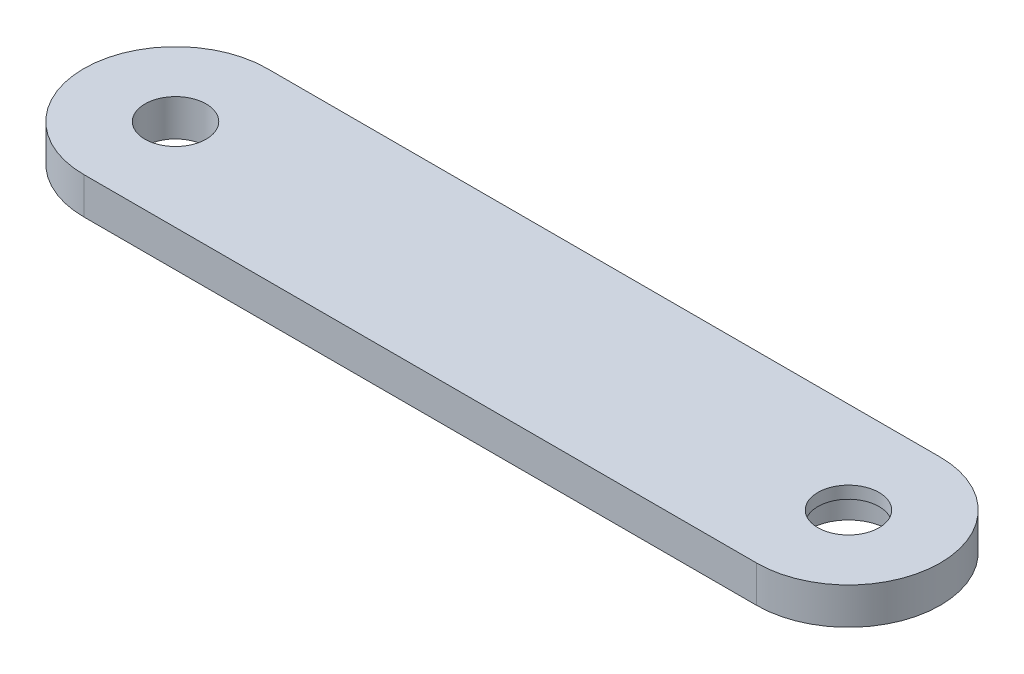
SolidWorks part; units mm, degrees
ref_plane "Front Plane" through (0, 0, 0) normal (0, 0, 1) x (1, 0, 0)
ref_plane "Top Plane" through (0, 0, 0) normal (0, 1, 0) x (1, 0, 0)
ref_plane "Right Plane" through (0, 0, 0) normal (1, 0, 0) x (0, 0, -1)
sketch "Sketch2" plane through (0, 0, 0) normal (0, 1, 0) x (1, 0, 0)
  line L1 (-45, 15) -> (65, 15)
  line L3 (-45, -15) -> (65, -15)
  arc A0 (-45, 15) -> (-45, -15) centre (-45, 0) ccw
  arc A1 (65, -15) -> (65, 15) centre (65, 0) ccw
  circle A2 centre (-45, 0) radius 5
  circle A3 centre (65, 0) radius 5
  point P0 (0, 0)
extrude "Boss-Extrude1" add sketch "Sketch2" along normal blind 6
sketch "Sketch3" plane through (0, 0, 0) normal (0, -1, 0) x (1, 0, 0)
  circle A0 centre (65, 0) radius 6.5
extrude "Cut-Extrude1" cut sketch "Sketch3" against normal blind 4
